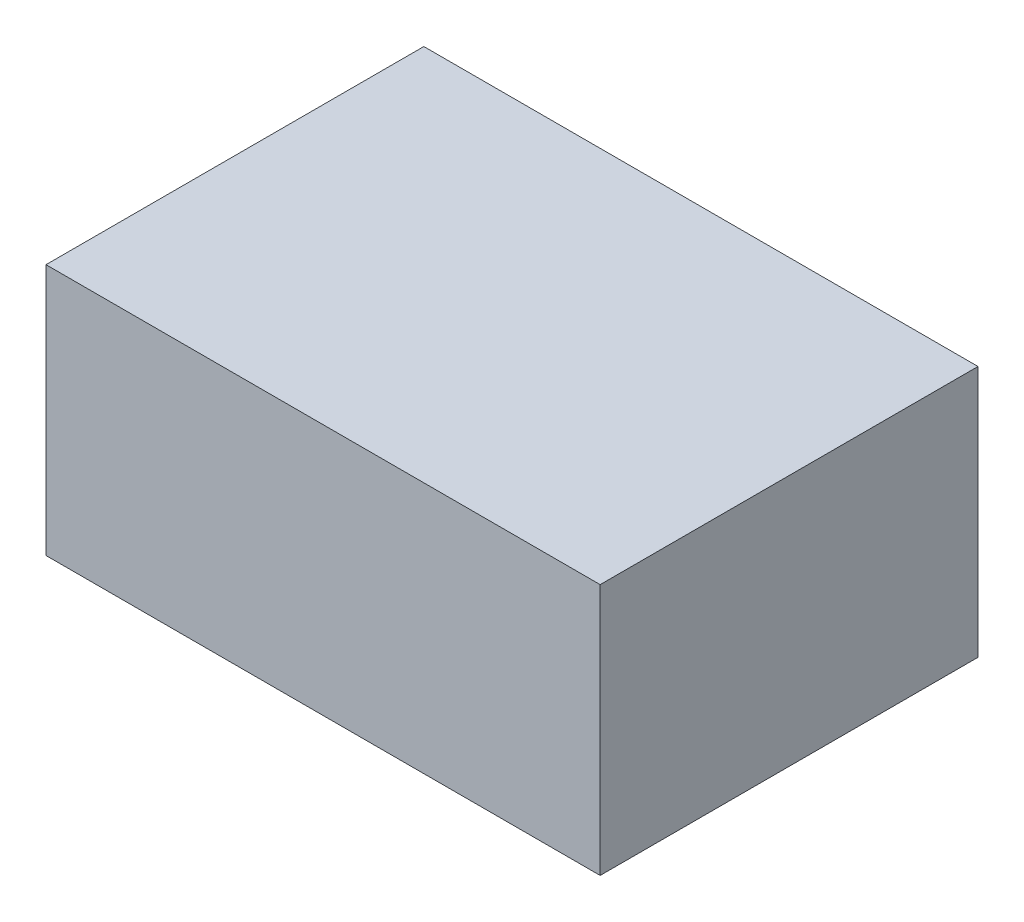
SolidWorks part; units mm, degrees
ref_plane "Front Plane" through (0, 0, 0) normal (0, 0, 1) x (1, 0, 0)
ref_plane "Top Plane" through (0, 0, 0) normal (0, 1, 0) x (1, 0, 0)
ref_plane "Right Plane" through (0, 0, 0) normal (1, 0, 0) x (0, 0, -1)
sketch "Sketch1" plane through (0, 0, 0) normal (0, 1, 0) x (1, 0, 0)
  line L1 (110, -75) -> (-110, -75)
  line L2 (110, -75) -> (110, 75)
  line L3 (110, 75) -> (-110, 75)
  line L4 (-110, -75) -> (-110, 75)
  line L5 (110, -75) -> (-110, 75) construction
  line L6 (110, 75) -> (-110, -75) construction
  point P0 (0, 0)
  dimension "D1" = 220
  dimension "D2" = 150
extrude "Boss-Extrude1" add sketch "Sketch1" along normal blind 100
